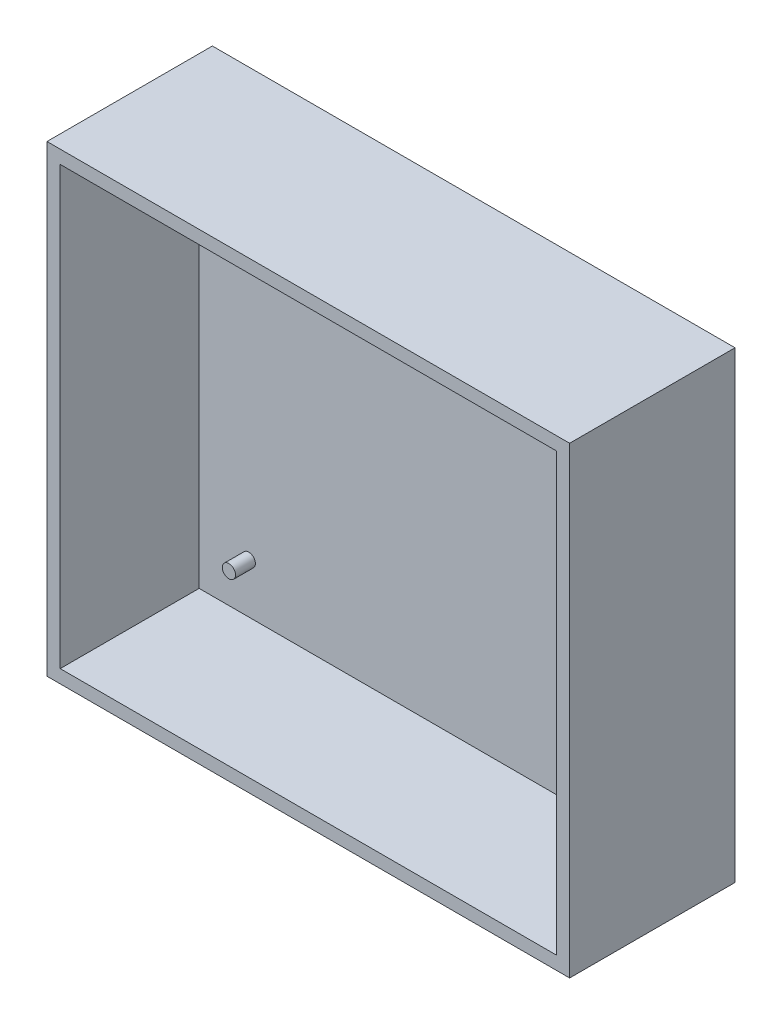
SolidWorks part; units mm, degrees
ref_plane "Plan de face" through (0, 0, 0) normal (0, 0, 1) x (1, 0, 0)
ref_plane "Plan de dessus" through (0, 0, 0) normal (0, 1, 0) x (1, 0, 0)
ref_plane "Plan de droite" through (0, 0, 0) normal (1, 0, 0) x (0, 0, -1)
sketch "Esquisse1" plane through (0, 0, 0) normal (0, 0, 1) x (1, 0, 0)
  line L1 (0, 0) -> (75, 0)
  line L2 (0, 0) -> (0, 66)
  line L3 (0, 66) -> (75, 66)
  line L4 (75, 0) -> (75, 66)
  dimension "D1" = 66
  dimension "D2" = 75
extrude "Boss.-Extru.1" add sketch "Esquisse1" along normal blind 4
sketch "Esquisse2" plane through (0, 0, 4) normal (0, 0, 1) x (1, 0, 0)
  line L0 (75, 0) -> (75, 66) construction
  line L1 (0, 0) -> (75, 0) construction
  line L2 (0, 33) -> (75, 33) construction
  line L3 (0, 66) -> (0, 0) construction
  line L4 (37.5, 66) -> (37.5, 0) construction
  line L5 (75, 66) -> (0, 66) construction
  circle A0 centre (67.5, 7.5) radius 1
  circle A1 centre (67.5, 58.5) radius 1
  circle A2 centre (7.5, 58.5) radius 1
  circle A3 centre (7.5, 7.5) radius 1
  dimension "D1" = 2
  dimension "D2" = 7.5
  dimension "D3" = 7.5
extrude "Boss.-Extru.2" add sketch "Esquisse2" along normal blind 3
sketch "Esquisse3" plane through (0, 0, 0) normal (0, 0, -1) x (-1, 0, 0)
  line L8 (2, -2) -> (2, 68)
  line L9 (2, 68) -> (-77, 68)
  line L10 (-77, 68) -> (-77, -2)
  line L11 (-77, -2) -> (2, -2)
  line L12 (2, -2) -> (2, 68)
  line L13 (2, 68) -> (-77, 68)
  line L14 (-77, 68) -> (-77, -2)
  line L15 (-77, -2) -> (2, -2)
  line L16 (0, 0) -> (0, 66)
  line L17 (0, 66) -> (-75, 66)
  line L18 (-75, 66) -> (-75, 0)
  line L19 (-75, 0) -> (0, 0)
  line L20 (0, 0) -> (0, 66)
  line L21 (0, 66) -> (-75, 66)
  line L22 (-75, 66) -> (-75, 0)
  line L23 (-75, 0) -> (0, 0)
  dimension "D1" = 2
  dimension "D2" = 0
extrude "Boss.-Extru.3" add sketch "Esquisse3" against normal blind 25
